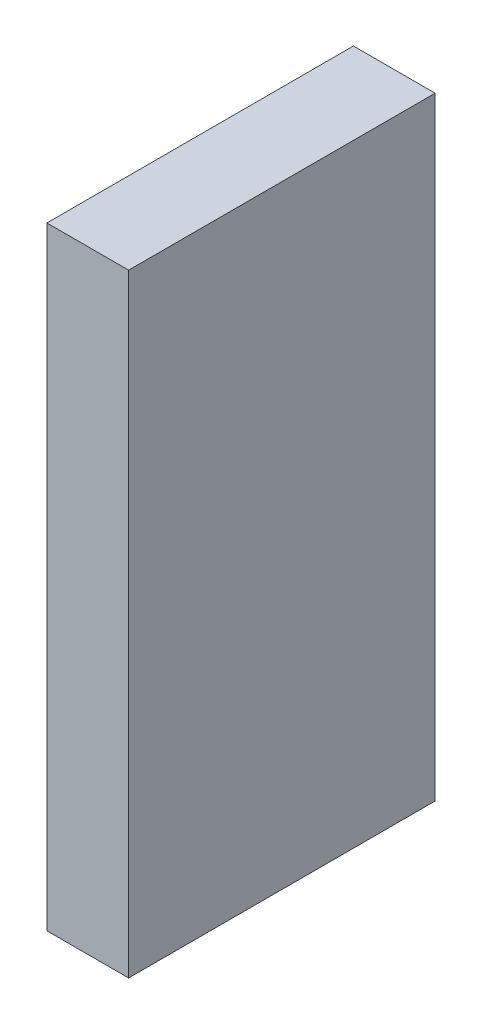
SolidWorks part; units mm, degrees
ref_plane "Front Plane" through (0, 0, 0) normal (0, 0, 1) x (1, 0, 0)
ref_plane "Top Plane" through (0, 0, 0) normal (0, 1, 0) x (1, 0, 0)
ref_plane "Right Plane" through (0, 0, 0) normal (1, 0, 0) x (0, 0, -1)
other "Configuration Table"
sketch "Sketch1" plane through (0, 0, 0) normal (0, 0, 1) x (1, 0, 0)
  line L1 (546, 700) -> (554, 700)
  line L2 (546, 700) -> (546, 760)
  line L3 (546, 760) -> (554, 760)
  line L4 (554, 700) -> (554, 760)
extrude "PACK_flap_parmagi_3_1" add sketch "Sketch1" against normal blind 30 from offset 185 separate body
